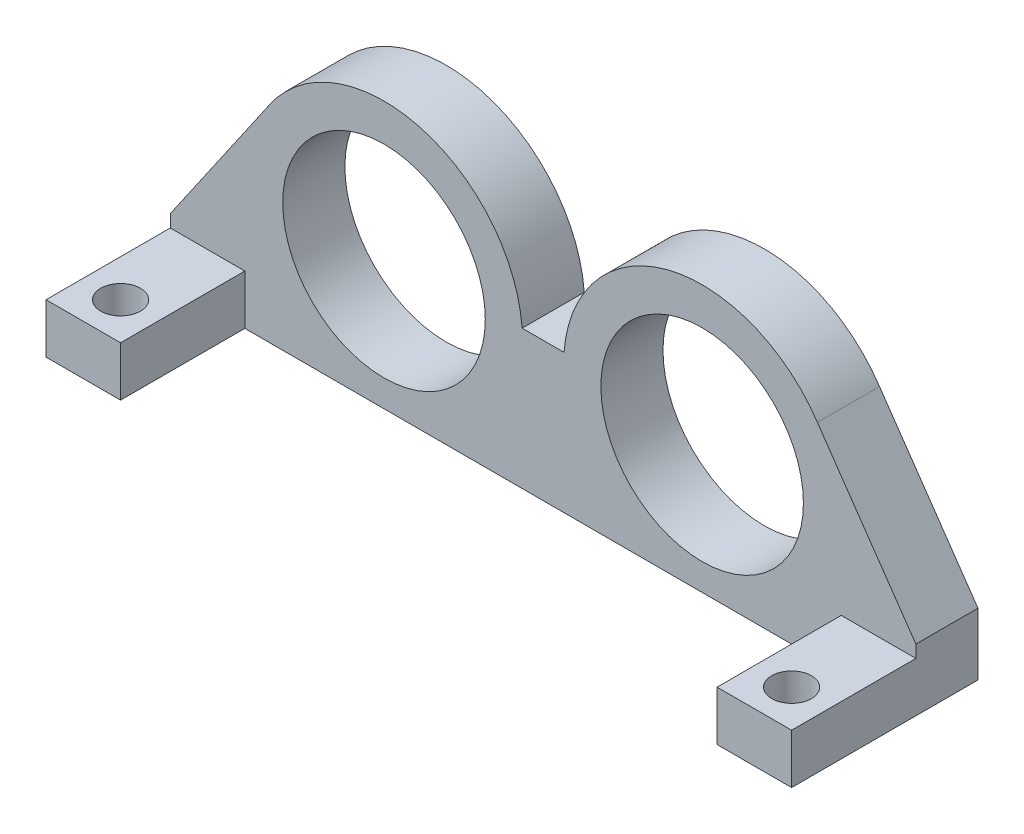
SolidWorks part; units mm, degrees
ref_plane "Front" through (0, 0, 0) normal (0, 0, 1) x (1, 0, 0)
ref_plane "Top" through (0, 0, 0) normal (0, 1, 0) x (1, 0, 0)
ref_plane "Right" through (0, 0, 0) normal (1, 0, 0) x (0, 0, -1)
sketch "Sketch1" plane through (0, 0, 0) normal (0, 0, 1) x (1, 0, 0)
  line L0 (30, 0) -> (-30, 0)
  line L1 (-30, 0) -> (-30, 5)
  line L2 (-30, 5) -> (-22.0761, 16.4859)
  line L3 (-1.6844, 11.1748) -> (1.6844, 11.1748)
  line L4 (0, 35.1636) -> (0, -9.6944) construction
  line L5 (30, 5) -> (22.0761, 16.4859)
  line L6 (30, 0) -> (30, 5)
  arc A0 (-22.0761, 16.4859) -> (-1.6844, 11.1748) centre (-12.8, 10.2991) cw
  circle A1 centre (-12.8, 10.2991) radius 8.15
  circle A2 centre (12.8, 10.2991) radius 8.15
  arc A3 (22.0761, 16.4859) -> (1.6844, 11.1748) centre (12.8, 10.2991) ccw
  point P0 (-2.6269, 13.4504)
  point P21 (0, 11.1748)
  point P23 (0, 0)
  dimension "D1" = 16.3
  dimension "D5" = 3
  dimension "D2" = 12.8
  dimension "D3" = 60
  dimension "D4" = 5
extrude "Boss-Extrude1" add sketch "Sketch1" along normal blind 5
sketch "Sketch3" plane through (0, 0, 5) normal (0, 0, 1) x (1, 0, 0)
  line L0 (0, 24.744) -> (0, -26.2523) construction
  line L1 (-30, 0) -> (-24, 0)
  line L2 (-30, 0) -> (-30, 4)
  line L3 (-30, 4) -> (-24, 4)
  line L4 (-24, 0) -> (-24, 4)
  line L5 (24, 0) -> (24, 4)
  line L6 (30, 4) -> (24, 4)
  line L7 (30, 0) -> (30, 4)
  line L8 (30, 0) -> (24, 0)
  point P12 (23, 4)
  dimension "D1" = 4
  dimension "D2" = 6
extrude "Boss-Extrude2" add sketch "Sketch3" along normal blind 10
sketch "Sketch4" plane through (0, 4, 0) normal (0, 1, 0) x (1, 0, 0)
  line L1 (-24, -15) -> (-30, -15) construction
  line L2 (30, -15) -> (24, -15) construction
  circle A0 centre (-27, -12) radius 1.6
  circle A1 centre (27, -12) radius 1.6
  point P8 (-27, -15)
  point P9 (27, -15)
  point P10 (0, 0)
  dimension "D1" = 3.2
  dimension "D2" = 3.2
  dimension "D3" = 3
  dimension "D4" = 3
extrude "Cut-Extrude1" cut sketch "Sketch4" against normal blind 10
